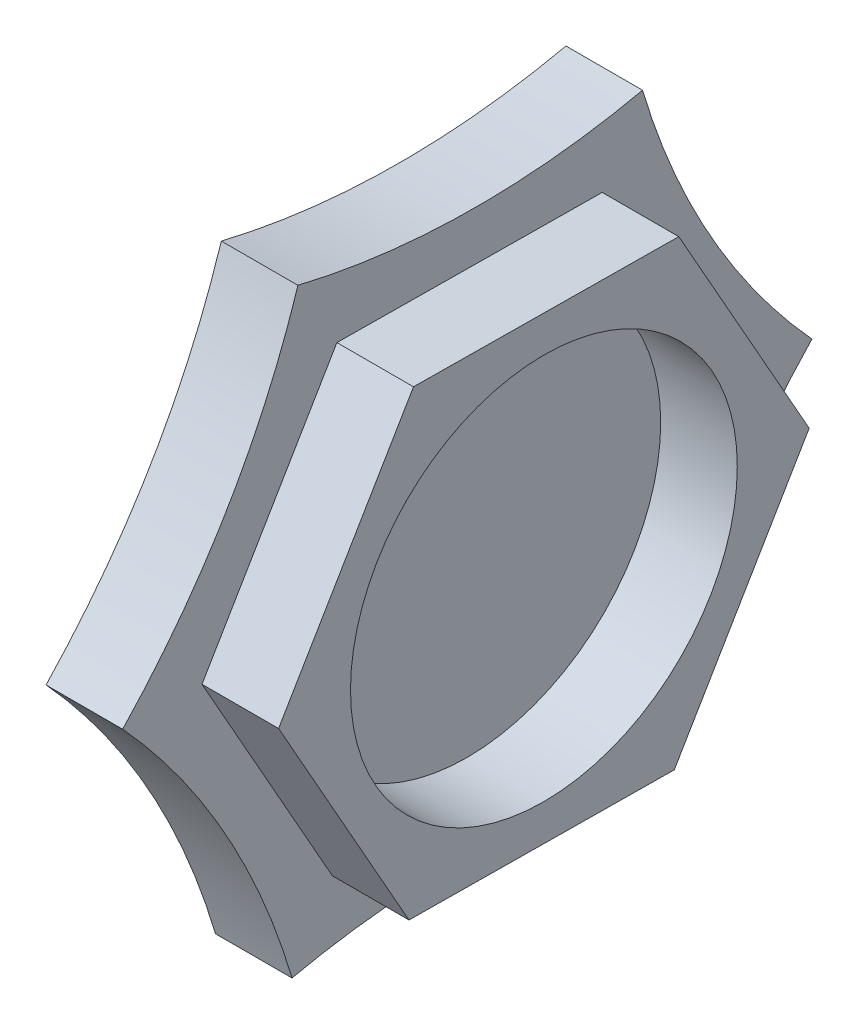
SolidWorks part; units mm, degrees
ref_plane "Front Plane" through (0, 0, 0) normal (0, 0, 1) x (1, 0, 0)
ref_plane "Top Plane" through (0, 0, 0) normal (0, 1, 0) x (1, 0, 0)
ref_plane "Right Plane" through (0, 0, 0) normal (1, 0, 0) x (0, 0, -1)
sketch "Sketch1" plane through (0, 0, 0) normal (1, 0, 0) x (0, 0, -1)
  line L1 (11.2355, -19.9096) -> (22.86, -0.2245) construction
  line L2 (22.86, -0.2245) -> (11.6245, 19.6851) construction
  line L3 (11.6245, 19.6851) -> (-11.2355, 19.9096) construction
  line L4 (-11.2355, 19.9096) -> (-22.86, 0.2245) construction
  line L5 (-22.86, 0.2245) -> (-11.6245, -19.6851) construction
  line L6 (-11.6245, -19.6851) -> (11.2355, -19.9096) construction
  circle A0 centre (0, 0) radius 19.7983 construction
  arc A1 (-11.6245, -19.6851) -> (11.2355, -19.9096) centre (-0.6806, -69.2923) cw
  arc A2 (-22.86, 0.2245) -> (-11.6245, -19.6851) centre (-60.3492, -34.0567) cw
  arc A3 (-11.2355, 19.9096) -> (-22.86, 0.2245) centre (-59.6685, 35.2356) cw
  arc A4 (11.6245, 19.6851) -> (-11.2355, 19.9096) centre (0.6806, 69.2923) cw
  arc A5 (22.86, -0.2245) -> (11.6245, 19.6851) centre (60.3492, 34.0567) cw
  arc A6 (11.2355, -19.9096) -> (22.86, -0.2245) centre (59.6685, -35.2356) cw
  dimension "D2" = 50.8
  dimension "D1" = 45.72
  dimension "D3" = 6
extrude "Boss-Extrude1" add sketch "Sketch1" along normal blind 5.08 contours A1 A6 A5 A4 A3 A2
ref_plane "Plane2" through (5.08, 0, 0) normal (1, 0, 0) x (0, 0, -1)
sketch "Sketch2" plane through (5.08, 0, 0) normal (1, 0, 0) x (0, 0, -1)
  line L1 (8.6487, -15.3257) -> (17.5968, -0.1728)
  line L2 (17.5968, -0.1728) -> (8.9481, 15.1528)
  line L3 (8.9481, 15.1528) -> (-8.6487, 15.3257)
  line L4 (-8.6487, 15.3257) -> (-17.5968, 0.1728)
  line L5 (-17.5968, 0.1728) -> (-8.9481, -15.1528)
  line L6 (-8.9481, -15.1528) -> (8.6487, -15.3257)
  circle A0 centre (0, 0) radius 15.24 construction
  dimension "D1" = 30.48
extrude "Boss-Extrude2" add sketch "Sketch2" along normal blind 5.08 from surface at 0 starting at plane "Plane2"
sketch "Sketch3" plane through (10.16, 0, 0) normal (1, 0, 0) x (0, 0, -1)
  circle A0 centre (0, 0) radius 12.827
  dimension "D1" = 25.654
extrude "Cut-Extrude1" cut sketch "Sketch3" against normal blind 5.08
ref_plane "Plane1" through (5.08, 0, 0) normal (1, 0, 0) x (0, 0, -1)
sketch "Sketch4" plane through (0, 0, 0) normal (-1, 0, 0) x (0, 0, 1)
  line L0 (-22.86, -0.2245) -> (22.86, 0.2245) construction
  line L1 (-17.831, -6.4213) -> (17.7237, -6.4213) construction
  arc A0 (-11.2355, -19.9096) -> (-22.86, -0.2245) centre (-59.6685, -35.2356) ccw construction
  arc A1 (22.86, 0.2245) -> (11.6245, -19.6851) centre (60.3492, -34.0567) ccw construction
  text T0 "<b>           Geneve's</b>"
  text T1 "<b>Rook</b>"
extrude "Cut-Extrude2" cut sketch "Sketch4" against normal blind 0.254
